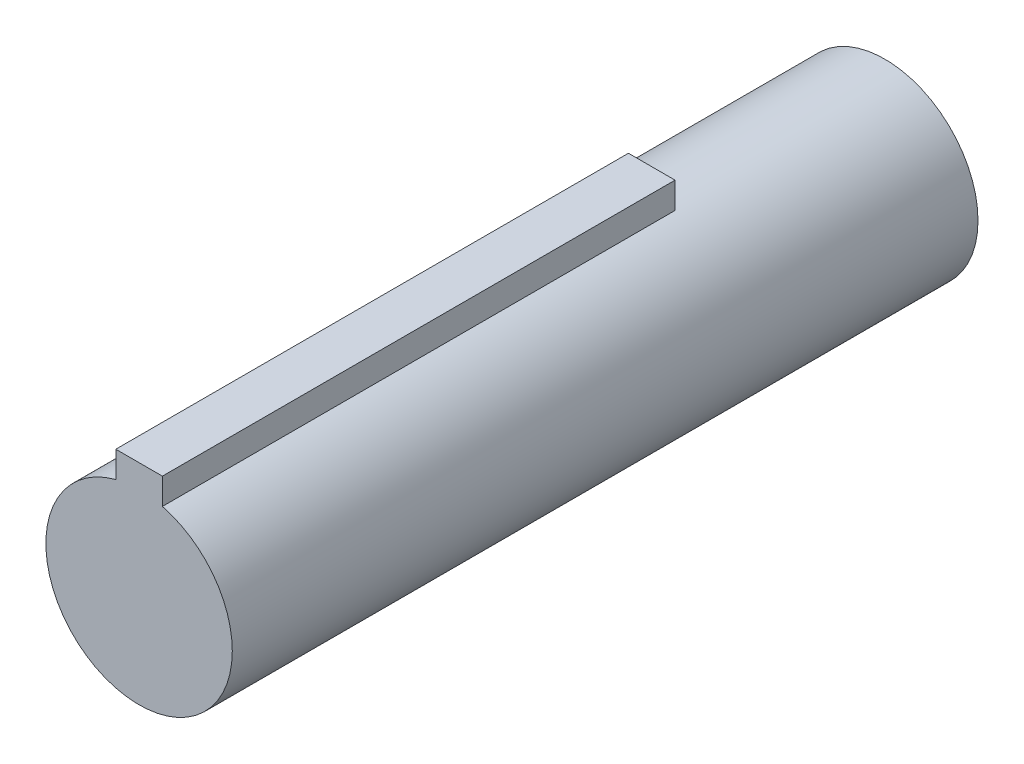
SolidWorks part; units mm, degrees
ref_plane "Front" through (0, 0, 0) normal (0, 0, 1) x (1, 0, 0)
ref_plane "Top" through (0, 0, 0) normal (0, 1, 0) x (1, 0, 0)
ref_plane "Right" through (0, 0, 0) normal (1, 0, 0) x (0, 0, -1)
sketch "Sketch1" plane through (0, 0, 0) normal (0, 0, 1) x (1, 0, 0)
  line L3 (-5, 25) -> (-5, 19.3649)
  line L4 (5, 25) -> (-5, 25)
  line L5 (5, 19.3649) -> (5, 25)
  arc A1 (-5, 19.3649) -> (5, 19.3649) centre (0, 0) ccw
extrude "Extrude1" add sketch "Sketch1" against normal blind 150 and the other way blind 10
sketch "Sketch2" plane through (0, 0, -150) normal (0, 0, -1) x (-1, 0, 0)
  line L0 (-5, 19.3649) -> (-5, 25) construction
  line L1 (-5, 25) -> (5, 25) construction
  line L2 (5, 25) -> (5, 19.3649) construction
  line L3 (-5, 19.3649) -> (-5, 25)
  line L4 (-5, 25) -> (5, 25)
  line L5 (5, 25) -> (5, 19.3649)
  arc A0 (-5, 19.3649) -> (5, 19.3649) centre (0, 0) ccw construction
  arc A1 (5, 19.3649) -> (-5, 19.3649) centre (0, 0) ccw
extrude "Cut-Extrude1" cut sketch "Sketch2" against normal blind 50
